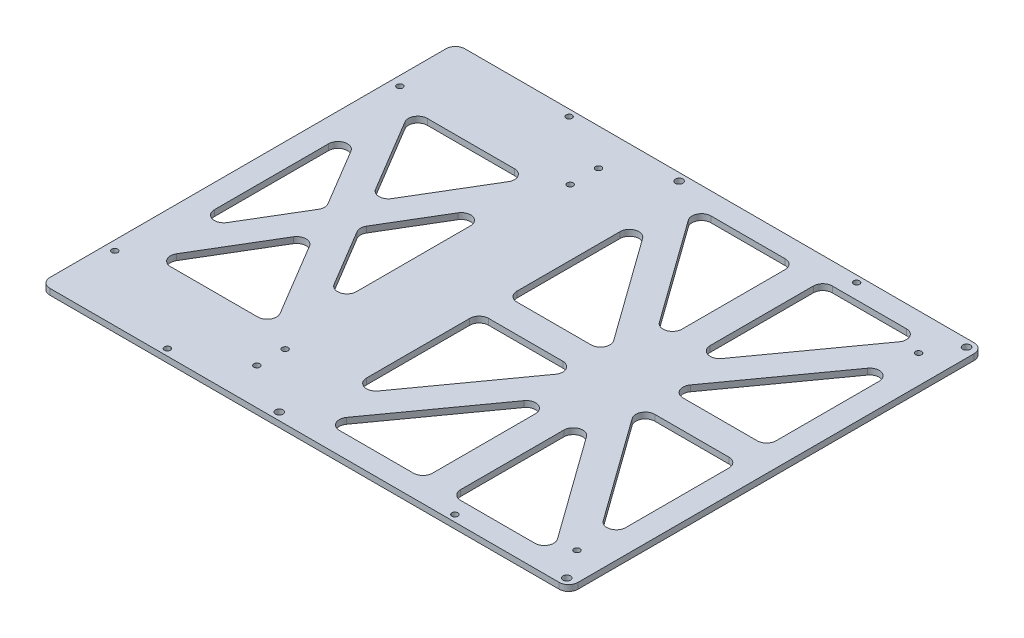
SolidWorks part; units mm, degrees
ref_plane "Front Plane" through (0, 0, 0) normal (0, 0, 1) x (1, 0, 0)
ref_plane "Top Plane" through (0, 0, 0) normal (0, 1, 0) x (1, 0, 0)
ref_plane "Right Plane" through (0, 0, 0) normal (1, 0, 0) x (0, 0, -1)
sketch "Sketch1" plane through (0, 0, 0) normal (0, 1, 0) x (1, 0, 0)
  line L0 (-280, 0) -> (280, 0) construction
  line L1 (-280, -210) -> (-280, 210)
  line L2 (-270, -220) -> (270, -220)
  line L3 (280, -210) -> (280, 210)
  line L4 (-270, 220) -> (270, 220)
  line L5 (0, -220) -> (0, 220) construction
  circle A0 centre (-152.4, -213) radius 3.175
  arc A1 (-270, -220) -> (-280, -210) centre (-270, -210) cw
  circle A2 centre (-152.4, 213) radius 3.175
  circle A3 centre (152.4, 213) radius 3.175
  circle A4 centre (152.4, -213) radius 3.175
  arc A5 (270, -220) -> (280, -210) centre (270, -210) ccw
  arc A6 (280, 210) -> (270, 220) centre (270, 210) ccw
  arc A7 (-280, 210) -> (-270, 220) centre (-270, 210) cw
  point P8 (0, 0)
  dimension "D5" = 6.35
  dimension "D6" = 10
  dimension "D7" = 10
  dimension "D1" = 560
  dimension "D2" = 440
  dimension "D3" = 213
  dimension "D4" = 152.4
extrude "Body" add sketch "Sketch1" along normal blind 6.35
sketch "Sketch3" plane through (0, 6.35, 0) normal (0, 1, 0) x (1, 0, 0)
  line L0 (117.6, -211.98) -> (117.6, 211.98) construction
  line L1 (-34.8, -211.98) -> (-34.8, 211.98) construction
  line L2 (-34.8, -211.98) -> (270, -211.98) construction
  line L3 (270, -211.98) -> (270, 211.98) construction
  line L4 (-34.8, 211.98) -> (270, 211.98) construction
  line L5 (280, -210) -> (280, 210) construction
  circle A0 centre (-34.8, -211.98) radius 4
  circle A1 centre (270, -211.98) radius 4
  circle A2 centre (270, 211.98) radius 4
  circle A3 centre (-34.8, 211.98) radius 4
  point P10 (117.6, 0)
  dimension "D3" = 8
  dimension "D1" = 423.96
  dimension "D2" = 304.8
  dimension "D4" = 10
sketch "Sketch5" plane through (0, 6.35, 0) normal (0, 1, 0) x (1, 0, 0)
  line L0 (-270, -151.13) -> (-89.43, -151.13) construction
  line L1 (-89.43, -151.13) -> (-89.43, 151.13) construction
  line L2 (-89.43, 151.13) -> (-270, 151.13) construction
  line L3 (-270, 151.13) -> (-270, -151.13) construction
  line L4 (-270, 0) -> (-89.43, 0) construction
  line L6 (-280, 210) -> (-280, -210) construction
  circle A0 centre (-270, -151.13) radius 3.175
  circle A1 centre (-270, 151.13) radius 3.175
  circle A2 centre (-89.43, -151.13) radius 3.175
  circle A3 centre (-89.43, 151.13) radius 3.175
  dimension "D3" = 6.35
  dimension "D1" = 302.26
  dimension "D2" = 180.57
  dimension "D4" = 10
extrude "Electronics Box" cut sketch "Sketch3" against normal up to next
extrude "Battery Charger" cut sketch "Sketch5" against normal up to next
sketch "Sketch6" plane through (0, 6.35, 0) normal (0, 1, 0) x (1, 0, 0)
  line L0 (-255, 60.5351) -> (-255, -60.5351)
  line L1 (-236.4152, -65.6636) -> (-200.2516, -5.1285)
  line L2 (-200.2516, 5.1285) -> (-236.4152, 65.6636)
  line L3 (-179.715, 151.13) -> (-179.715, -151.13) construction
  line L4 (-89.43, 0) -> (-270, 0) construction
  line L5 (-159.1784, 5.1285) -> (-123.0148, 65.6636)
  line L6 (-234.5284, -121.0015) -> (-188.2998, -43.6183)
  line L7 (-171.1302, -43.6183) -> (-124.9016, -121.0015)
  line L8 (-133.4864, -136.13) -> (-225.9436, -136.13)
  line L9 (-270, 151.13) -> (-89.43, 151.13) construction
  line L10 (-89.43, 151.13) -> (-89.43, -151.13) construction
  line L11 (-89.43, -151.13) -> (-270, -151.13) construction
  line L12 (-270, -151.13) -> (-270, 151.13) construction
  line L13 (-89.43, 151.13) -> (-270, -151.13) construction
  line L14 (-89.43, -151.13) -> (-270, 151.13) construction
  line L15 (-123.0148, -65.6636) -> (-159.1784, -5.1285)
  line L16 (-104.43, 60.5351) -> (-104.43, -60.5351)
  line L17 (-171.1302, 43.6183) -> (-124.9016, 121.0015)
  line L18 (-234.5284, 121.0015) -> (-188.2998, 43.6183)
  line L19 (-133.4864, 136.13) -> (-225.9436, 136.13)
  line L20 (-34.8, 211.98) -> (270, 211.98) construction
  line L21 (270, 211.98) -> (270, -211.98) construction
  line L22 (270, -211.98) -> (-34.8, -211.98) construction
  line L23 (-34.8, -211.98) -> (-34.8, 211.98) construction
  line L24 (117.6, 211.98) -> (117.6, -211.98) construction
  line L25 (270, 0) -> (-34.8, 0) construction
  line L26 (-34.8, 211.98) -> (270, -211.98) construction
  line L27 (270, 211.98) -> (-34.8, -211.98) construction
  line L28 (-1.6806, 140.2161) -> (76.9557, 30.8374)
  line L29 (-9.8, 15) -> (68.8363, 15)
  line L30 (-19.8, 25) -> (-19.8, 134.3788)
  line L31 (255, 25) -> (255, 134.3788)
  line L32 (245, 15) -> (166.3637, 15)
  line L33 (236.8806, 140.2161) -> (158.2443, 30.8374)
  line L34 (84.4806, 71.7639) -> (5.8443, 181.1426)
  line L35 (13.9637, 196.98) -> (92.6, 196.98)
  line L36 (221.2363, 196.98) -> (142.6, 196.98)
  line L37 (132.6, 77.6012) -> (132.6, 186.98)
  line L38 (150.7194, 71.7639) -> (229.3557, 181.1426)
  line L39 (102.6, -77.6012) -> (102.6, -186.98)
  line L40 (102.6, 77.6012) -> (102.6, 186.98)
  line L41 (150.7194, -71.7639) -> (229.3557, -181.1426)
  line L42 (132.6, -77.6012) -> (132.6, -186.98)
  line L43 (221.2363, -196.98) -> (142.6, -196.98)
  line L44 (13.9637, -196.98) -> (92.6, -196.98)
  line L45 (84.4806, -71.7639) -> (5.8443, -181.1426)
  line L46 (236.8806, -140.2161) -> (158.2443, -30.8374)
  line L47 (245, -15) -> (166.3637, -15)
  line L48 (255, -25) -> (255, -134.3788)
  line L49 (-19.8, -25) -> (-19.8, -134.3788)
  line L50 (-9.8, -15) -> (68.8363, -15)
  line L51 (-1.6806, -140.2161) -> (76.9557, -30.8374)
  arc A2 (-255, 60.5351) -> (-236.4152, 65.6636) centre (-245, 60.5351) cw
  arc A3 (-236.4152, -65.6636) -> (-255, -60.5351) centre (-245, -60.5351) cw
  arc A4 (-200.2516, 5.1285) -> (-200.2516, -5.1285) centre (-208.8364, 0) cw
  arc A5 (-159.1784, 5.1285) -> (-159.1784, -5.1285) centre (-150.5936, 0) ccw
  arc A6 (-104.43, 60.5351) -> (-123.0148, 65.6636) centre (-114.43, 60.5351) ccw
  arc A7 (-123.0148, -65.6636) -> (-104.43, -60.5351) centre (-114.43, -60.5351) ccw
  arc A8 (-225.9436, -136.13) -> (-234.5284, -121.0015) centre (-225.9436, -126.13) cw
  arc A9 (-124.9016, -121.0015) -> (-133.4864, -136.13) centre (-133.4864, -126.13) cw
  arc A10 (-188.2998, -43.6183) -> (-171.1302, -43.6183) centre (-179.715, -48.7469) cw
  arc A11 (-124.9016, 121.0015) -> (-133.4864, 136.13) centre (-133.4864, 126.13) ccw
  arc A12 (-188.2998, 43.6183) -> (-171.1302, 43.6183) centre (-179.715, 48.7469) ccw
  arc A13 (-225.9436, 136.13) -> (-234.5284, 121.0015) centre (-225.9436, 126.13) ccw
  arc A14 (-1.6806, 140.2161) -> (-19.8, 134.3788) centre (-9.8, 134.3788) ccw
  arc A15 (-9.8, 15) -> (-19.8, 25) centre (-9.8, 25) cw
  arc A16 (68.8363, 15) -> (76.9557, 30.8374) centre (68.8363, 25) ccw
  arc A17 (166.3637, 15) -> (158.2443, 30.8374) centre (166.3637, 25) cw
  arc A18 (245, 15) -> (255, 25) centre (245, 25) ccw
  arc A19 (236.8806, 140.2161) -> (255, 134.3788) centre (245, 134.3788) cw
  arc A20 (13.9637, 196.98) -> (5.8443, 181.1426) centre (13.9637, 186.98) ccw
  arc A21 (102.6, 77.6012) -> (84.4806, 71.7639) centre (92.6, 77.6012) cw
  arc A22 (92.6, 196.98) -> (102.6, 186.98) centre (92.6, 186.98) cw
  arc A23 (221.2363, 196.98) -> (229.3557, 181.1426) centre (221.2363, 186.98) cw
  arc A24 (142.6, 196.98) -> (132.6, 186.98) centre (142.6, 186.98) ccw
  arc A25 (132.6, 77.6012) -> (150.7194, 71.7639) centre (142.6, 77.6012) ccw
  arc A26 (132.6, -77.6012) -> (150.7194, -71.7639) centre (142.6, -77.6012) cw
  arc A27 (142.6, -196.98) -> (132.6, -186.98) centre (142.6, -186.98) cw
  arc A28 (221.2363, -196.98) -> (229.3557, -181.1426) centre (221.2363, -186.98) ccw
  arc A29 (92.6, -196.98) -> (102.6, -186.98) centre (92.6, -186.98) ccw
  arc A30 (102.6, -77.6012) -> (84.4806, -71.7639) centre (92.6, -77.6012) ccw
  arc A31 (13.9637, -196.98) -> (5.8443, -181.1426) centre (13.9637, -186.98) cw
  arc A32 (236.8806, -140.2161) -> (255, -134.3788) centre (245, -134.3788) ccw
  arc A33 (245, -15) -> (255, -25) centre (245, -25) cw
  arc A34 (166.3637, -15) -> (158.2443, -30.8374) centre (166.3637, -25) ccw
  arc A35 (68.8363, -15) -> (76.9557, -30.8374) centre (68.8363, -25) cw
  arc A36 (-9.8, -15) -> (-19.8, -25) centre (-9.8, -25) ccw
  arc A37 (-1.6806, -140.2161) -> (-19.8, -134.3788) centre (-9.8, -134.3788) cw
  dimension "D7" = 10
  dimension "D8" = 10
  dimension "D11" = 10
  dimension "D14" = 10
  dimension "D15" = 10
  dimension "D18" = 10
  dimension "D1" = 15
  dimension "D2" = 15
  dimension "D3" = 15
  dimension "D4" = 15
  dimension "D5" = 15
  dimension "D6" = 15
  dimension "D9" = 15
  dimension "D10" = 15
  dimension "D12" = 15
  dimension "D13" = 15
  dimension "D16" = 15
  dimension "D17" = 15
extrude "Fillets" cut sketch "Sketch6" against normal up to next
sketch "Sketch7" plane through (0, 6.35, 0) normal (0, 1, 0) x (1, 0, 0)
  line L0 (280, -210) -> (280, 210) construction
  line L1 (0, 0) -> (280, 0) construction
  circle A0 centre (250, 181.13) radius 3.175
  circle A1 centre (-89.43, 181.13) radius 3.175
  circle A4 centre (-89.43, -181.13) radius 3.175
  circle A5 centre (250, -181.13) radius 3.175
  point P4 (-89.43, 151.13)
  dimension "D2" = 6.35
  dimension "D1" = 30
  dimension "D3" = 30
extrude "Plant Mounting holes" cut sketch "Sketch7" against normal up to next
